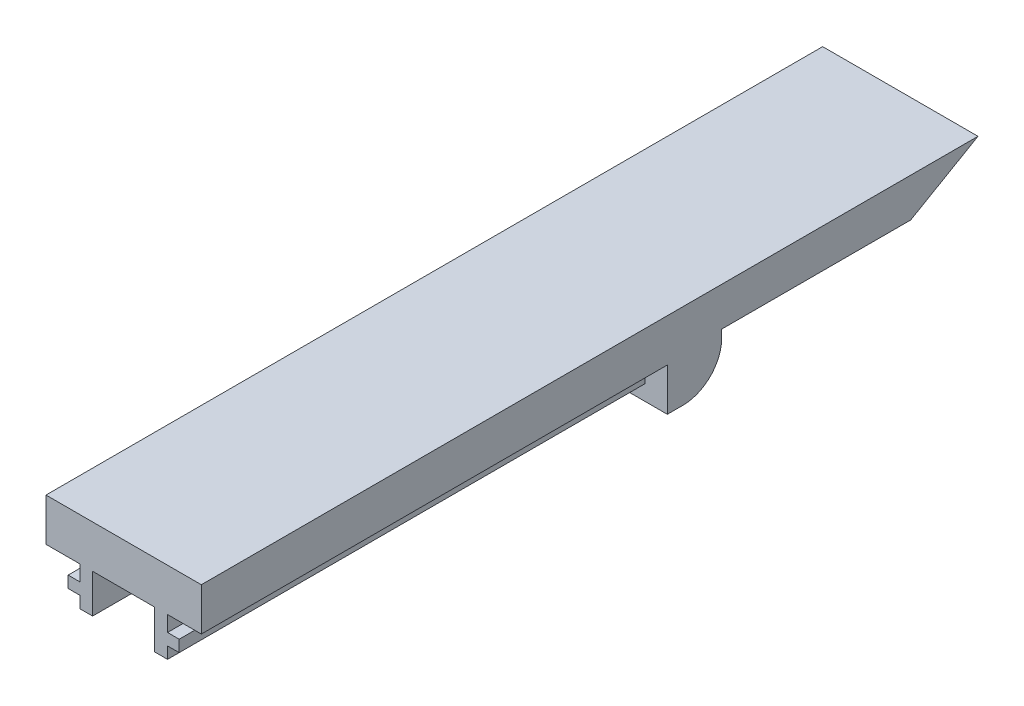
SolidWorks part; units mm, degrees
ref_plane "Front Plane" through (0, 0, 0) normal (0, 0, 1) x (1, 0, 0)
ref_plane "Top Plane" through (0, 0, 0) normal (0, 1, 0) x (1, 0, 0)
ref_plane "Right Plane" through (0, 0, 0) normal (1, 0, 0) x (0, 0, -1)
sketch "Sketch1" plane through (0, 0, 0) normal (0, 0, 1) x (1, 0, 0)
  line L1 (-26.5363, 10.2235) -> (-6.5363, 10.2235)
  line L2 (-26.5363, 10.2235) -> (-26.5363, 2.2235)
  line L3 (-26.5363, 2.2235) -> (-6.5363, 2.2235)
  line L4 (-6.5363, 10.2235) -> (-6.5363, 2.2235)
  dimension "D1" = 20
  dimension "D2" = 8
extrude "Boss-Extrude1" add sketch "Sketch1" against normal blind 100
sketch "Sketch2" plane through (0, 0, 0) normal (0, 0, 1) x (1, 0, 0)
  line L0 (-26.5363, 10.2235) -> (-26.5363, 2.2235) construction
  line L1 (-26.5363, 7.7235) -> (-22.1863, 7.7235)
  line L2 (-22.1863, 7.7235) -> (-22.1863, 5.7235)
  line L3 (-22.1863, 5.7235) -> (-23.6863, 5.7235)
  line L4 (-23.6863, 5.7235) -> (-23.6863, 4.2235)
  line L5 (-23.6863, 4.2235) -> (-22.1863, 4.2235)
  line L6 (-22.1863, 4.2235) -> (-22.1863, 2.7235)
  line L7 (-22.1863, 2.7235) -> (-20.5363, 2.7235)
  line L8 (-20.5363, 2.7235) -> (-20.5363, 7.7235)
  line L9 (-20.5363, 7.7235) -> (-12.5363, 7.7235)
  line L10 (-16.5363, 10.2235) -> (-16.5363, 5.2831) construction
  line L11 (-6.5363, 10.2235) -> (-26.5363, 10.2235) construction
  line L13 (-26.5363, 7.7235) -> (-26.5363, 2.2235)
  line L15 (-12.5363, 2.7235) -> (-12.5363, 7.7235)
  line L16 (-10.8863, 2.7235) -> (-12.5363, 2.7235)
  line L17 (-10.8863, 4.2235) -> (-10.8863, 2.7235)
  line L18 (-9.3863, 4.2235) -> (-10.8863, 4.2235)
  line L19 (-9.3863, 5.7235) -> (-9.3863, 4.2235)
  line L20 (-10.8863, 5.7235) -> (-9.3863, 5.7235)
  line L21 (-10.8863, 7.7235) -> (-10.8863, 5.7235)
  line L22 (-6.5363, 7.7235) -> (-10.8863, 7.7235)
  line L23 (-6.5363, 7.7235) -> (-6.5363, 2.2235)
  line L24 (-26.5363, 2.2235) -> (-6.5363, 2.2235)
  point P23 (-16.5363, 7.7235)
  dimension "D2" = 2.5
  dimension "D3" = 4.35
  dimension "D4" = 2
  dimension "D5" = 1.5
  dimension "D6" = 1.5
  dimension "D7" = 1.5
  dimension "D8" = 1.65
extrude "Cut-Extrude1" cut sketch "Sketch2" against normal blind 60
sketch "Sketch3" plane through (0, 10.2235, 0) normal (0, 1, 0) x (1, 0, 0)
  line L4 (-26.5363, 0) -> (-6.5363, 0)
  line L5 (-6.5363, 0) -> (-6.5363, 100)
  line L6 (-6.5363, 100) -> (-26.5363, 100)
  line L7 (-26.5363, 100) -> (-26.5363, 0)
  line L8 (-26.5363, 0) -> (-6.5363, 0)
  line L9 (-6.5363, 0) -> (-6.5363, 100)
  line L10 (-6.5363, 100) -> (-26.5363, 100)
  line L11 (-26.5363, 100) -> (-26.5363, 0)
  dimension "D1" = 0
extrude "Boss-Extrude2" add sketch "Sketch3" along normal blind 3
ref_plane "Plane1" through (0, -33.3837, -19.2741) normal (0, 0.866, 0.5) x (-1, 0, 0)
sketch "Sketch13" plane through (0, -33.3837, -19.2741) normal (0, 0.866, 0.5) x (-1, 0, 0)
  line L5 (39.5856, -68.4) -> (-7.1505, -68.4)
  line L6 (39.5856, -68.4) -> (39.5856, -132.2421)
  line L7 (39.5856, -132.2421) -> (-7.1505, -132.2421)
  line L8 (-7.1505, -68.4) -> (-7.1505, -132.2421)
extrude "Cut-Extrude5" cut sketch "Sketch13" against normal blind 30
sketch "Sketch15" plane through (0, 2.2235, 0) normal (0, -1, 0) x (1, 0, 0)
  line L14 (-26.5363, -80.9474) -> (-26.5363, -60) construction
  line L15 (-26.5363, -67) -> (-6.5363, -67)
  line L16 (-26.5363, -67) -> (-26.5363, -97)
  line L17 (-26.5363, -97) -> (-6.5363, -97)
  line L18 (-6.5363, -67) -> (-6.5363, -97)
  line L19 (-6.5363, -80.9474) -> (-6.5363, -60) construction
  line L20 (-26.5363, -60) -> (-6.5363, -60) construction
  dimension "D1" = 7
  dimension "D2" = 30
extrude "Cut-Extrude6" cut sketch "Sketch15" against normal blind 6
fillet "Fillet1" radius 5 1 edges at (-16.5363, 2.2235, -67)
